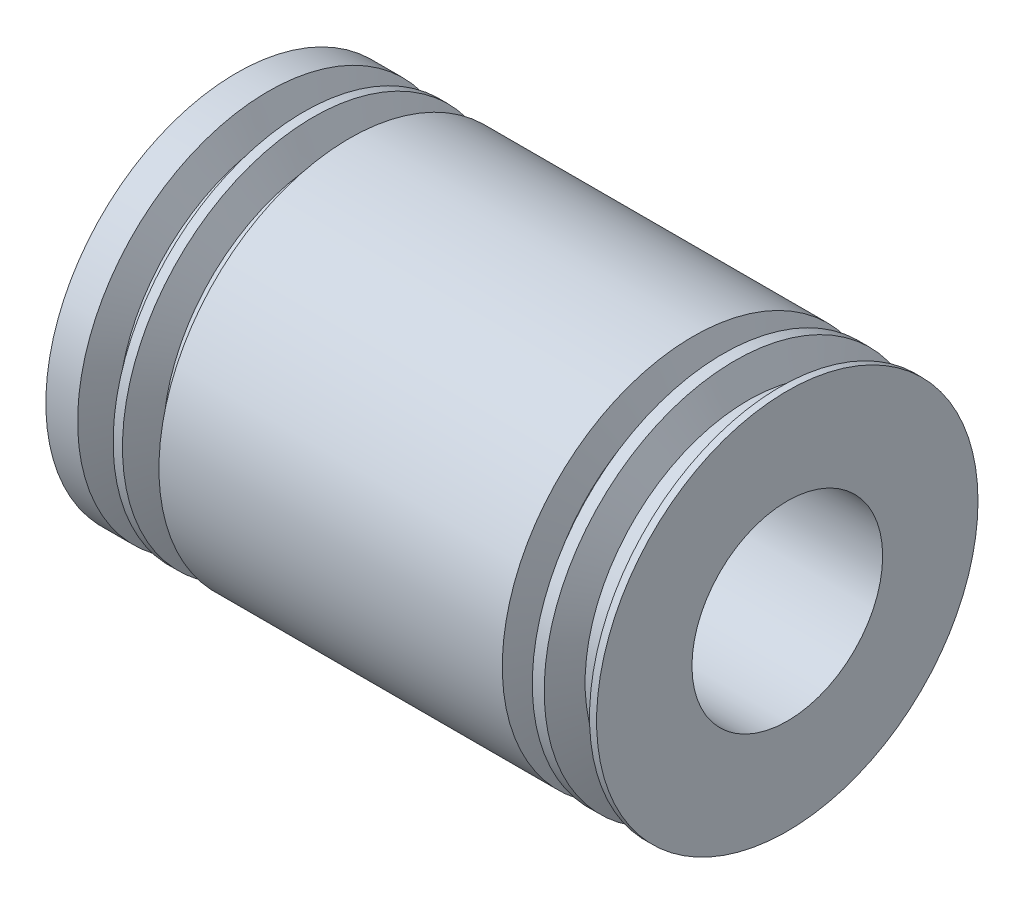
SolidWorks part; units mm, degrees
ref_plane "Płaszczyzna przednia" through (0, 0, 0) normal (0, 0, 1) x (1, 0, 0)
ref_plane "Płaszczyzna górna" through (0, 0, 0) normal (0, 1, 0) x (1, 0, 0)
ref_plane "Płaszczyzna prawa" through (0, 0, 0) normal (1, 0, 0) x (0, 0, -1)
sketch "Szkic1" plane through (0, 0, 0) normal (0, 0, 1) x (1, 0, 0)
  line L0 (0, 0) -> (-17, 0)
  line L1 (-17, 0) -> (-17, 3)
  line L2 (-17, 3) -> (-16, 3)
  line L3 (-16, 3) -> (-15.5864, 2.1326)
  line L4 (-15.5864, 2.1326) -> (-15.3637, 2.1326)
  line L5 (-15.3637, 2.1326) -> (-14.8837, 3)
  line L6 (-14.8837, 3) -> (-14.59, 3)
  line L7 (-14.59, 3) -> (-14.1764, 2.1326)
  line L11 (-0.3751, 2.1326) -> (0.1049, 3)
  line L12 (0.1049, 3) -> (0.3276, 3)
  line L13 (0.3276, 3) -> (0.3276, 0)
  line L14 (0.3276, 0) -> (0, 0)
  line L15 (0.3276, -3) -> (-3.999, -3)
  line L16 (-14.1764, 2.1326) -> (-13.9079, 2.1326)
  line L17 (-13.9079, 2.1326) -> (-13.4418, 3)
  line L18 (-0.3751, 2.1326) -> (-0.9017, 2.1326)
  line L19 (-0.9017, 2.1326) -> (-1.3211, 3)
  line L20 (-1.3211, 3) -> (-1.6956, 3)
  line L21 (-1.6956, 3) -> (-2.0083, 2.1326)
  line L22 (-2.0083, 2.1326) -> (-2.3247, 2.1326)
  line L23 (-2.3247, 2.1326) -> (-2.6393, 3)
  line L24 (-2.6393, 3) -> (-13.4418, 3)
  dimension "D1" = 3
  dimension "D2" = 3
  dimension "D3" = 17
  dimension "D4" = 1
revolve "Obrót1" add sketch "Szkic1" angle 360 about L15
